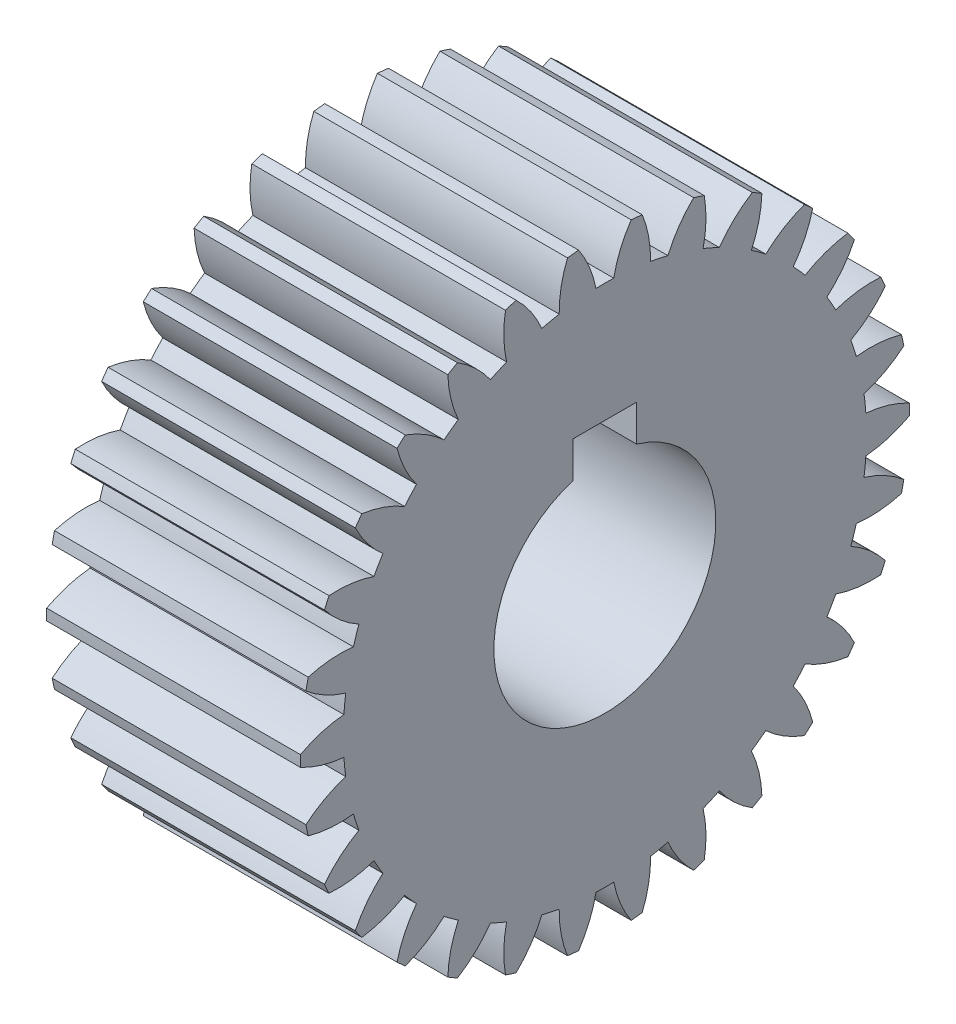
SolidWorks part; units mm, degrees
ref_plane "Plane1" through (0, 0, 0) normal (0, 0, 1) x (1, 0, 0)
ref_plane "Plane2" through (0, 0, 0) normal (0, 1, 0) x (1, 0, 0)
ref_plane "Plane3" through (0, 0, 0) normal (1, 0, 0) x (0, 0, -1)
sketch "HoldingSke" plane through (0, 0, 0) normal (0, 1, 0) x (1, 0, 0)
  line L0 (0, 0) -> (1.4434, -0.8333)
  line L1 (-15, 0) -> (100, 0) construction
  line L2 (0, 0) -> (-2.1039, 2.3779)
  line L3 (0, 0) -> (-11.863, 4.5341)
  line L4 (0, 0) -> (7.479, 4.318)
  line L5 (0, 0) -> (-46.8476, -17.4728)
  line L6 (0, 0) -> (-6.6317, -4.4744)
  line L7 (-2.1039, 2.3779) -> (8.6586, 51.2059)
  line L8 (-76.2, 54.61) -> (-75.2, 54.61)
  line L9 (-71.009, 38.7566) -> (-53.1078, 45.2721)
  line L10 (-76.2, 71.12) -> (104.1128, 71.12)
  line L11 (0, 0) -> (-8, 0)
  line L12 (-76.2, 101.6) -> (-76.177, 101.6)
  line L13 (24.9733, 27.94) -> (52.9518, 28.4284)
  line L14 (24.9733, 27.94) -> (24.9743, 27.94)
  line L15 (24.9733, 27.94) -> (100.4006, 29.5858)
  line L16 (-63.627, -0.6) -> (-12.827, -0.6)
  circle A0 centre (0, 0) radius 3.5
  circle A1 centre (0, 0) radius 8.249
  circle A2 centre (0, 0) radius 37.5
  circle A3 centre (0, 0) radius 3.5
  dimension "MHD" = 16.498
  dimension "Hub_dia" = 75
  dimension "Bore" = 7
  dimension "MBD" = 7
  dimension "Num_teeth" = 30
  dimension "Pitch" = 1.6667
  dimension "Overall_len" = 50
  dimension "Show_teeth" = 30
  dimension "Thickness" = 8
  dimension "OAL" = 50.0001
  dimension "T_dim" = 1
  dimension "Ap" = 20
  dimension "H" = 19.05
  dimension "Pitch_radius" = 180.3128
  dimension "Width" = 8
  dimension "Backlash" = 0.023
  dimension "Addendum_fac" = 1
  dimension "Dedendum_fac" = 1.25
  dimension "Clearance_fac" = 0.25
  dimension "Dedendum_add" = 0.001
  dimension "Module" = 0.6
sketch "BasProSke" plane through (0, 0, 0) normal (0, 1, 0) x (1, 0, 0)
  line L0 (-10, 0) -> (60, 0) construction
  line L1 (0, 0) -> (0, 9.6)
  line L2 (0, 0) -> (8, 0)
  line L3 (8, 0) -> (8, 9.6)
  line L4 (8, 9.6) -> (0, 9.6)
  dimension "Thickness" = 8
  dimension "Diameter" = 19.2
revolve "Base-Revolve" add sketch "BasProSke" angle 360 about L0
sketch "TooCutSke" plane through (0, 0, 0) normal (1, 0, 0) x (0, 0, -1)
  line L1 (0, 0) -> (0, 107) construction
  line L2 (0, 0) -> (-0.5113, 8.9855) construction
  line L3 (0, 0) -> (-1.8794, 17.8809) construction
  line L4 (-0.5113, 8.9855) -> (-0.9397, 8.9404) construction
  arc A0 (0.2801, 8.2442) -> (-0.2801, 8.2442) centre (0, 0) ccw
  arc A1 (0.8454, 9.5882) -> (-0.8454, 9.5882) centre (0, 0) ccw
  circle A2 centre (0, 0) radius 9 construction
  circle A3 centre (0, 0) radius 8.4572 construction
  arc A4 (-0.2801, 8.2442) -> (-0.8454, 9.5882) centre (-3.8124, 7.5492) ccw
  arc A5 (0.8454, 9.5882) -> (0.2801, 8.2442) centre (3.8124, 7.5492) ccw
  dimension "Root_dia" = 16.498
  dimension "Overcut_dia" = 19.2508
  dimension "Pitch_dia" = 18
  dimension "Base_dia" = 16.9145
  dimension "Flank_rad" = 3.6
  dimension "Half_ang" = 6
  dimension "Half_CT" = 0.4308
extrude "ToothCut" cut sketch "TooCutSke" along normal through all
fillet "Breaks" [suppressed] radius 0.012
fillet "RootFillets" [suppressed] radius 0.151
pattern_circular "TeethCuts" count 30 every 12 about axis through (-10, 0, 0) along (1, 0, 0) of "ToothCut", "RootFillets", "Breaks"
sketch "HubNeaOneSke" plane through (0, 0, 0) normal (-1, 0, 0) x (0, 0, 1)
  circle A0 centre (0, 0) radius 8.249
  dimension "Diameter" = 16.498
extrude "HubNearOne" [suppressed] add sketch "HubNeaOneSke" along normal blind 42.0001
sketch "HubNeaBotSke" plane through (0, 0, 0) normal (-1, 0, 0) x (0, 0, 1)
  circle A0 centre (0, 0) radius 8.249
  dimension "Diameter" = 16.498
extrude "HubNearBoth" [suppressed] add sketch "HubNeaBotSke" along normal blind 21
ref_plane "FarPln" through (8, 0, 0) normal (1, 0, 0) x (0, 0, -1)
sketch "HubFarSke" plane through (8, 0, 0) normal (1, 0, 0) x (0, 0, -1)
  circle A0 centre (0, 0) radius 8.249
  dimension "Diameter" = 16.498
extrude "HubFar" [suppressed] add sketch "HubFarSke" along normal blind 21
sketch "BorSke" plane through (0, 0, 0) normal (1, 0, 0) x (0, 0, -1)
  circle A0 centre (0, 0) radius 3.5
  dimension "Diameter" = 7
extrude "Bore" cut sketch "BorSke" along normal mid plane 100.0001
sketch "KeySke" plane through (0, 0, 0) normal (1, 0, 0) x (0, 0, -1)
  line L0 (-1, 0) -> (-1, 4.5)
  line L1 (-1, 4.5) -> (1, 4.5)
  line L2 (1, 4.5) -> (1, 0)
  line L3 (0, 0) -> (0, 34) construction
  line L4 (-1, 0) -> (1, 0)
  dimension "Offset" = 4.5
  dimension "Width" = 2
extrude "Keyway" cut sketch "KeySke" along normal mid plane 100.0001
pattern_circular "Keyway2" [suppressed] count 2 every 90 about axis through (-10, 0, 0) along (1, 0, 0)
equation "' \"Module@HoldingSke\" = 6.35"
equation "' \"Num_teeth@HoldingSke\" = 12"
equation "' \"Ap@HoldingSke\" =  20"
equation "' \"Ap@HoldingSke\" = 20"
equation "' \"Width@HoldingSke\" = 0.5 * 25.4"
equation "' \"Hub_dia@HoldingSke\"= 1 * 25.4"
equation "' \"Hub_dia@HoldingSke\" = 1 * 25.4"
equation "' \"Overall_len@HoldingSke\" = 1.0 * 25.4"
equation "' \"Bore@HoldingSke\" = 0.75 * 25.4"
equation "' \"T_dim@HoldingSke\" = 0.1 * 25.4"
equation "' \"Width@KeySke\" = 0.25 * 25.4"
equation "' \"Show_teeth@HoldingSke\" = 13"
equation "' \"Backlash@HoldingSke\" = 0.009 * 25.4"
equation "' \"Addendum_fac@HoldingSke\" = 1.0"
equation "' \"Dedendum_fac@HoldingSke\" = 1.25"
equation "' \"Dedendum_add@HoldingSke\" = 0.00005 * 25.4"
equation "' \"Clearance_fac@HoldingSke\" = 0.25"
equation "\"Pitch@HoldingSke\" = 1 / \"Module@HoldingSke\""
equation "\"Overcut_dia@TooCutSke\" = (\"Num_teeth@HoldingSke\" + 2 * \"Addendum_fac@HoldingSke\") / \"Pitch@HoldingSke\" + 0.002 * 25.4"
equation "\"Pitch_dia@TooCutSke\" = \"Num_teeth@HoldingSke\" / \"Pitch@HoldingSke\""
equation "\"Base_dia@TooCutSke\" = \"Num_teeth@HoldingSke\" / \"Pitch@HoldingSke\" * cos((\"Ap@HoldingSke\"  * 3.14159265 / 180))"
equation "\"Root_dia@TooCutSke\" = (\"Num_teeth@HoldingSke\" + 2) / \"Pitch@HoldingSke\" - 2 * (\"Addendum_fac@HoldingSke\" + \"Dedendum_fac@HoldingSke\") / \"Pitch@HoldingSke\" - \"Dedendum_add@HoldingSke\" * 2"
equation "\"Half_ang@TooCutSke\" = 180 / \"Num_teeth@HoldingSke\""
equation "\"Half_CT@TooCutSke\" = \"Num_teeth@HoldingSke\" / \"Pitch@HoldingSke\" * sin((3.14159265 / 2 / \"Num_teeth@HoldingSke\")) / 2 - 7 * \"Backlash@HoldingSke\" / 4"
equation "\"Flank_rad@TooCutSke\" = \"Num_teeth@HoldingSke\" / \"Pitch@HoldingSke\" / 5"
equation "\"Radius@RootFillets\" = \"Clearance_fac@HoldingSke\" / \"Pitch@HoldingSke\" + \"Dedendum_add@HoldingSke\""
equation "\"Break_rad@Breaks\" = 0.02 / \"Pitch@HoldingSke\""
equation "\"Thickness@HoldingSke\" = \"Width@HoldingSke\""
equation "\"OAL@HoldingSke\" = \"Thickness@HoldingSke\""
equation "\"MHD@HoldingSke\" = (\"Num_teeth@HoldingSke\" + 2) / \"Pitch@HoldingSke\" - 2 * (\"Addendum_fac@HoldingSke\" + \"Dedendum_fac@HoldingSke\")  / \"Pitch@HoldingSke\" - \"Dedendum_add@HoldingSke\" * 2"
equation "\"MBD@HoldingSke\" = (\"Num_teeth@HoldingSke\" + 2) / \"Pitch@HoldingSke\" - 2 * (\"Addendum_fac@HoldingSke\" + \"Dedendum_fac@HoldingSke\")  / \"Pitch@HoldingSke\" - \"Dedendum_add@HoldingSke\" * 2 - 0.002 * 25.4"
equation "\"MHD@HoldingSke\" = ((sgn( \"MHD@HoldingSke\" - \"Hub_dia@HoldingSke\" )-1)*( \"MHD@HoldingSke\" - \"Hub_dia@HoldingSke\" ))/-2+ \"Hub_dia@HoldingSke\""
equation "\"MBD@HoldingSke\" = ((sgn( \"MBD@HoldingSke\" - \"Bore@HoldingSke\" )-1)*( \"MBD@HoldingSke\" - \"Bore@HoldingSke\" ))/-2+ \"Bore@HoldingSke\""
equation "\"OAL@HoldingSke\" = ((sgn( \"OAL@HoldingSke\" - \"Overall_len@HoldingSke\" )+1)*( \"OAL@HoldingSke\" - \"Overall_len@HoldingSke\" ))/2 + \"Overall_len@HoldingSke\" + 0.000002 * 25.4"
equation "\"Num_teeth@TeethCuts\" = int( \"Show_teeth@HoldingSke\" ) + 1"
equation "\"Num_teeth@TeethCuts\" = ((sgn( \"Num_teeth@TeethCuts\" - \"Num_teeth@HoldingSke\" )-1)*( \"Num_teeth@TeethCuts\" - \"Num_teeth@HoldingSke\" ))/-2+ \"Num_teeth@HoldingSke\""
equation "\"Num_teeth@TeethCuts\" = ((sgn( \"Num_teeth@TeethCuts\" - 2.0)+1)*( \"Num_teeth@TeethCuts\" - 2.0))/2 +2.0"
equation "\"Angle@TeethCuts\" = 360.0 / \"Num_teeth@HoldingSke\""
equation "\"Diameter@BasProSke\" = (\"Num_teeth@HoldingSke\" + 2 * \"Addendum_fac@HoldingSke\") / \"Pitch@HoldingSke\""
equation "\"Thickness@BasProSke\"  = \"Thickness@HoldingSke\""
equation "' \"Fillet_rad@BasProSke\" =  \"Thickness@HoldingSke\" * 0.05"
equation "' \"Fillet_rad@BasProSke\" = \"Thickness@HoldingSke\" * 0.05"
equation "\"MHD@HoldingSke\" = ((sgn( \"MHD@HoldingSke\" - \"Root_dia@TooCutSke\" )-1)*( \"MHD@HoldingSke\" - \"Root_dia@TooCutSke\" ))/-2+ \"Root_dia@TooCutSke\""
equation "\"Diameter@HubNeaOneSke\" = \"MHD@HoldingSke\""
equation "\"Length@HubNearOne\" = \"OAL@HoldingSke\" - \"Thickness@BasProSke\""
equation "\"Diameter@HubNeaBotSke\" = \"MHD@HoldingSke\""
equation "\"Length@HubNearBoth\" = ( \"OAL@HoldingSke\" - \"Thickness@BasProSke\" ) / 2.0"
equation "\"Thickness@FarPln\" = \"Thickness@BasProSke\""
equation "\"Diameter@HubFarSke\" = \"MHD@HoldingSke\""
equation "\"Length@HubFar\" = ( \"OAL@HoldingSke\" - \"Thickness@BasProSke\" ) / 2.0"
equation "\"Diameter@BorSke\" = \"MBD@HoldingSke\""
equation "\"D1@Bore\" = \"OAL@HoldingSke\" * 2.0"
equation "\"D1@Keyway\" = \"OAL@HoldingSke\" * 2.0"
equation "\"Offset@KeySke\" = \"T_dim@HoldingSke\" + \"MBD@HoldingSke\" / 2.0"
